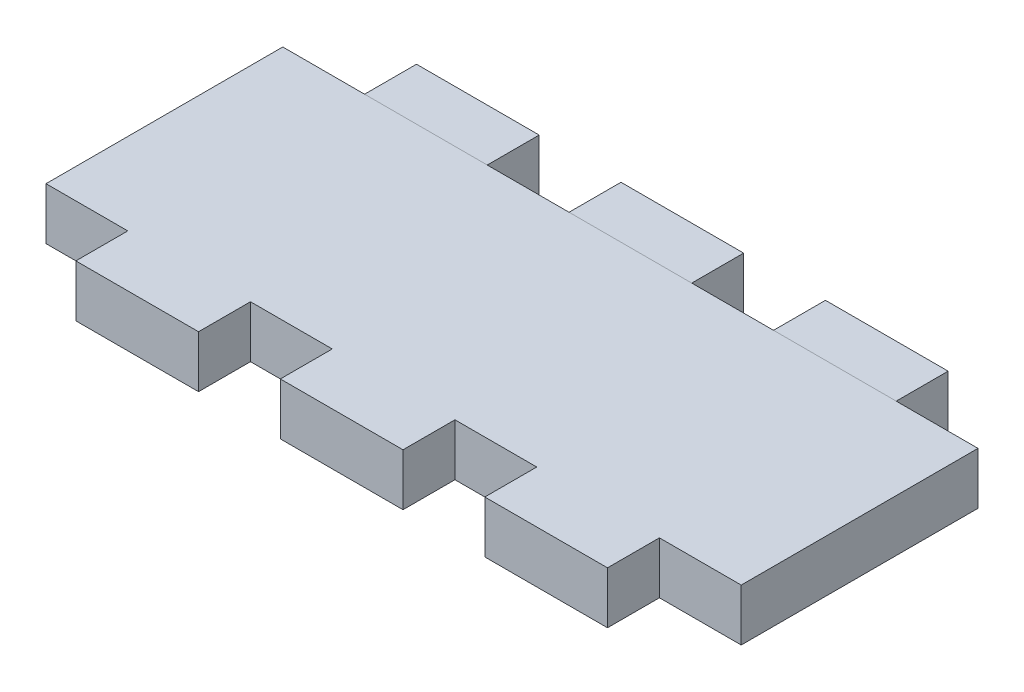
SolidWorks part; units mm, degrees
ref_plane "Plan de face" through (0, 0, 0) normal (0, 0, 1) x (1, 0, 0)
ref_plane "Plan de dessus" through (0, 0, 0) normal (0, 1, 0) x (1, 0, 0)
ref_plane "Plan de droite" through (0, 0, 0) normal (1, 0, 0) x (0, 0, -1)
sketch "Esquisse1" plane through (0, 0, 0) normal (0, 1, 0) x (1, 0, 0)
  line L1 (-42.5, -14.475) -> (42.5, -14.475)
  line L2 (-42.5, -14.475) -> (-42.5, 14.475)
  line L3 (-42.5, 14.475) -> (42.5, 14.475)
  line L4 (42.5, -14.475) -> (42.5, 14.475)
  line L5 (-42.5, -14.475) -> (42.5, 14.475) construction
  line L6 (-42.5, 14.475) -> (42.5, -14.475) construction
  point P0 (0, 0)
  dimension "D1" = 28.95
  dimension "D2" = 85
extrude "Boss.-Extru.1" add sketch "Esquisse1" along normal blind 6.35
sketch "Esquisse2" plane through (0, 6.35, 0) normal (0, 1, 0) x (1, 0, 0)
  line L0 (42.5, 14.475) -> (-42.5, 14.475) construction
  line L2 (-32.5, 14.475) -> (-17.5, 14.475)
  line L3 (-32.5, 14.475) -> (-32.5, 20.825)
  line L4 (-32.5, 20.825) -> (-17.5, 20.825)
  line L5 (-17.5, 14.475) -> (-17.5, 20.825)
  line L14 (-7.5, 14.475) -> (7.5, 14.475)
  line L15 (-7.5, 14.475) -> (-7.5, 20.825)
  line L16 (-7.5, 20.825) -> (7.5, 20.825)
  line L17 (7.5, 14.475) -> (7.5, 20.825)
  line L19 (17.5, 14.475) -> (32.5, 14.475)
  line L20 (17.5, 14.475) -> (17.5, 20.825)
  line L21 (17.5, 20.825) -> (32.5, 20.825)
  line L22 (32.5, 14.475) -> (32.5, 20.825)
  point P15 (0, 14.475)
  dimension "D1" = 6.35
  dimension "D2" = 15
  dimension "D3" = 10
  dimension "D4" = 10
extrude "Boss.-Extru.2" add sketch "Esquisse2" against normal blind 6.35 separate body
mirror "Symétrie1" about plane through (0, 0, 0) normal (0, 0, 1) of "Boss.-Extru.2"
